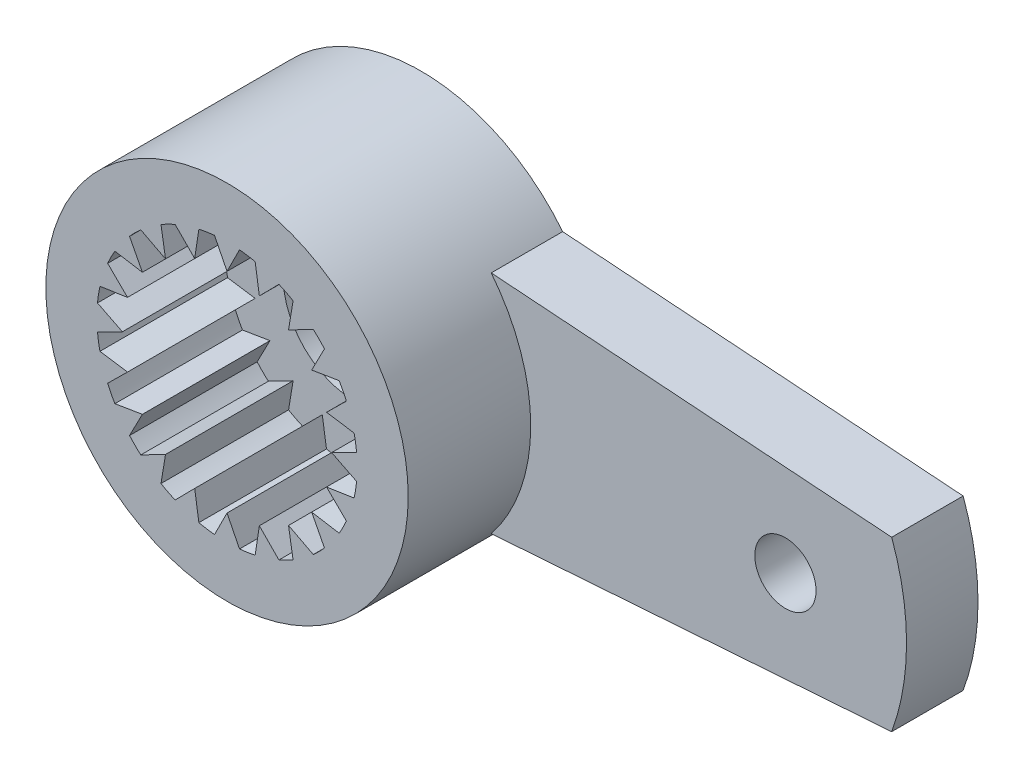
SolidWorks part; units mm, degrees
ref_plane "Front Plane" through (0, 0, 0) normal (0, 0, 1) x (1, 0, 0)
ref_plane "Top Plane" through (0, 0, 0) normal (0, 1, 0) x (1, 0, 0)
ref_plane "Right Plane" through (0, 0, 0) normal (1, 0, 0) x (0, 0, -1)
sketch "Sketch2" plane through (0, 0, 0) normal (0, 0, 1) x (1, 0, 0)
  circle A0 centre (0, 0) radius 3.55
  dimension "D1" = 7.1
sketch "Sketch3" plane through (0, 0, 0) normal (0, 0, 1) x (1, 0, 0)
  line L0 (-0.2447, 2.5382) -> (0, 2.05)
  line L1 (0, 2.05) -> (0.2447, 2.5382)
  line L2 (0.5516, 2.4896) -> (0.6335, 1.9497)
  line L3 (0.6335, 1.9497) -> (1.0171, 2.3384)
  line L4 (1.294, 2.1973) -> (1.205, 1.6585)
  line L5 (1.205, 1.6585) -> (1.6899, 1.9096)
  line L6 (1.9096, 1.6899) -> (1.6585, 1.205)
  line L7 (1.6585, 1.205) -> (2.1973, 1.294)
  line L8 (2.3384, 1.0171) -> (1.9497, 0.6335)
  line L9 (1.9497, 0.6335) -> (2.4896, 0.5516)
  line L10 (2.5382, 0.2447) -> (2.05, 0)
  line L11 (2.05, 0) -> (2.5382, -0.2447)
  line L12 (2.4896, -0.5516) -> (1.9497, -0.6335)
  line L13 (1.9497, -0.6335) -> (2.3384, -1.0171)
  line L14 (2.1973, -1.294) -> (1.6585, -1.205)
  line L15 (1.6585, -1.205) -> (1.9096, -1.6899)
  line L16 (1.6899, -1.9096) -> (1.205, -1.6585)
  line L17 (1.205, -1.6585) -> (1.294, -2.1973)
  line L18 (1.0171, -2.3384) -> (0.6335, -1.9497)
  line L19 (0.6335, -1.9497) -> (0.5516, -2.4896)
  line L20 (0.2447, -2.5382) -> (0, -2.05)
  line L21 (0, -2.05) -> (-0.2447, -2.5382)
  line L22 (-0.5516, -2.4896) -> (-0.6335, -1.9497)
  line L23 (-0.6335, -1.9497) -> (-1.0171, -2.3384)
  line L24 (-1.294, -2.1973) -> (-1.205, -1.6585)
  line L25 (-1.205, -1.6585) -> (-1.6899, -1.9096)
  line L26 (-1.9096, -1.6899) -> (-1.6585, -1.205)
  line L27 (-1.6585, -1.205) -> (-2.1973, -1.294)
  line L28 (-2.3384, -1.0171) -> (-1.9497, -0.6335)
  line L29 (-1.9497, -0.6335) -> (-2.4896, -0.5516)
  line L30 (-2.5382, -0.2447) -> (-2.05, 0)
  line L31 (-2.05, 0) -> (-2.5382, 0.2447)
  line L32 (-2.4896, 0.5516) -> (-1.9497, 0.6335)
  line L33 (-1.9497, 0.6335) -> (-2.3384, 1.0171)
  line L34 (-2.1973, 1.294) -> (-1.6585, 1.205)
  line L35 (-1.6585, 1.205) -> (-1.9096, 1.6899)
  line L36 (-1.6899, 1.9096) -> (-1.205, 1.6585)
  line L37 (-1.205, 1.6585) -> (-1.294, 2.1973)
  line L38 (-1.0171, 2.3384) -> (-0.6335, 1.9497)
  line L39 (-0.6335, 1.9497) -> (-0.5516, 2.4896)
  arc A0 (-0.2447, 2.5382) -> (0.2447, 2.5382) centre (0, 0) cw
  arc A2 (0.5516, 2.4896) -> (1.0171, 2.3384) centre (0, 0) cw
  arc A3 (1.294, 2.1973) -> (1.6899, 1.9096) centre (0, 0) cw
  arc A4 (1.9096, 1.6899) -> (2.1973, 1.294) centre (0, 0) cw
  arc A5 (2.3384, 1.0171) -> (2.4896, 0.5516) centre (0, 0) cw
  arc A6 (2.5382, 0.2447) -> (2.5382, -0.2447) centre (0, 0) cw
  arc A7 (2.4896, -0.5516) -> (2.3384, -1.0171) centre (0, 0) cw
  arc A8 (2.1973, -1.294) -> (1.9096, -1.6899) centre (0, 0) cw
  arc A9 (1.6899, -1.9096) -> (1.294, -2.1973) centre (0, 0) cw
  arc A10 (1.0171, -2.3384) -> (0.5516, -2.4896) centre (0, 0) cw
  arc A11 (0.2447, -2.5382) -> (-0.2447, -2.5382) centre (0, 0) cw
  arc A12 (-0.5516, -2.4896) -> (-1.0171, -2.3384) centre (0, 0) cw
  arc A13 (-1.294, -2.1973) -> (-1.6899, -1.9096) centre (0, 0) cw
  arc A14 (-1.9096, -1.6899) -> (-2.1973, -1.294) centre (0, 0) cw
  arc A15 (-2.3384, -1.0171) -> (-2.4896, -0.5516) centre (0, 0) cw
  arc A16 (-2.5382, -0.2447) -> (-2.5382, 0.2447) centre (0, 0) cw
  arc A17 (-2.4896, 0.5516) -> (-2.3384, 1.0171) centre (0, 0) cw
  arc A18 (-2.1973, 1.294) -> (-1.9096, 1.6899) centre (0, 0) cw
  arc A19 (-1.6899, 1.9096) -> (-1.294, 2.1973) centre (0, 0) cw
  arc A20 (-1.0171, 2.3384) -> (-0.5516, 2.4896) centre (0, 0) cw
  point P66 (0, 0)
  dimension "D1" = 20
ref_plane "Plane1" through (0, 0, -2.4) normal (0, 0, 1) x (1, 0, 0)
sketch "Sketch4" plane through (0, 0, -2.4) normal (0, 0, 1) x (1, 0, 0)
  line L0 (2.7764, 2.2123) -> (10.6226, 1.65)
  line L1 (2.7764, -2.2123) -> (10.6226, -1.65)
  arc A0 (10.6226, 1.65) -> (10.6226, -1.65) centre (6.0891, 0) cw
  arc A1 (2.7764, 2.2123) -> (2.7764, -2.2123) centre (0, 0) cw
  point P9 (10.6226, 1.65)
extrude "Boss-Extrude1" add sketch "Sketch2" against normal blind 3.8 contours A0
extrude "Boss-Extrude2" add sketch "Sketch4" against normal blind 1.4
sketch "Sketch5" plane through (0, 0, 0) normal (0, 0, 1) x (1, 0, 0)
  circle A0 centre (0, 0) radius 2.55
extrude "Cut-Extrude1" cut sketch "Sketch5" against normal blind 2.5
extrude "Boss-Extrude3" add sketch "Sketch3" against normal up to surface (2.5 mm away) up to face at (2.55, 0, -2.5)
sketch "Sketch6" plane through (0, 0, -2.5) normal (0, 0, 1) x (1, 0, 0)
  circle A0 centre (0, 0) radius 1.4
  dimension "D1" = 2.8
extrude "Cut-Extrude2" cut sketch "Sketch6" against normal through all
sketch "Sketch7" plane through (0, 0, -2.4) normal (0, 0, 1) x (1, 0, 0)
  circle A0 centre (8.5405, 0) radius 0.6
  dimension "D1" = 1.2
extrude "Cut-Extrude3" cut sketch "Sketch7" against normal through all
